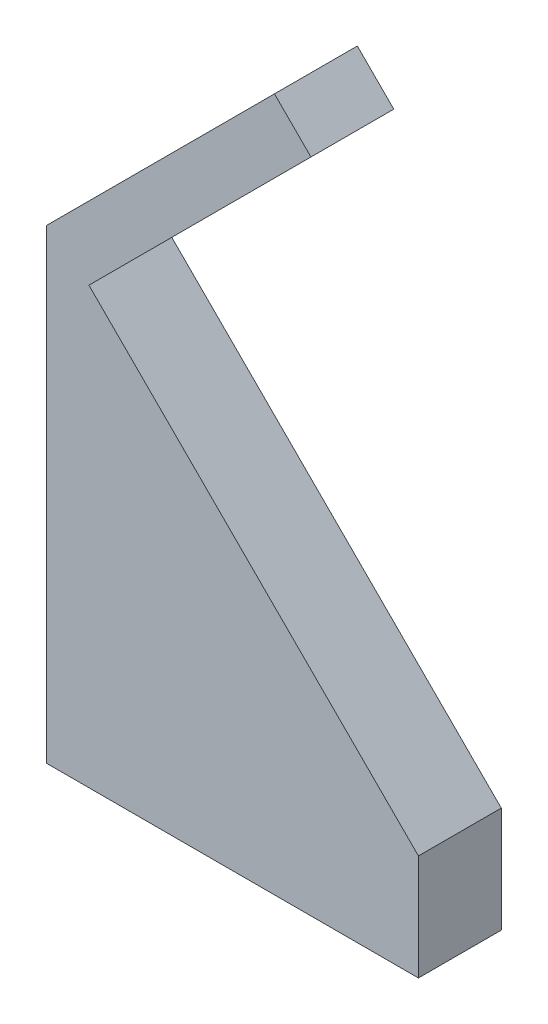
SolidWorks part; units mm, degrees
ref_plane "Alzado" through (0, 0, 0) normal (0, 0, 1) x (1, 0, 0)
ref_plane "Planta" through (0, 0, 0) normal (0, 1, 0) x (1, 0, 0)
ref_plane "Vista lateral" through (0, 0, 0) normal (1, 0, 0) x (0, 0, -1)
sketch "Croquis1" plane through (0, 0, 0) normal (0, 0, 1) x (1, 0, 0)
  line L0 (0, 61.867) -> (0, -61.867) construction
  line L1 (-5, 52.5879) -> (5, 52.5879) construction
  line L2 (-5, 52.5879) -> (-5, -52.5879) construction
  line L3 (-5, -52.5879) -> (5, -52.5879) construction
  line L4 (5, 52.5879) -> (5, -52.5879) construction
  line L5 (-5, 52.5879) -> (5, -52.5879) construction
  line L6 (-5, -52.5879) -> (5, 52.5879) construction
  line L7 (-5, -39.7902) -> (-5, -50)
  line L10 (-5, -50) -> (-40.8947, -50)
  line L11 (-40.8947, -5.0014) -> (-40.8947, -50)
  line L12 (-5, -39.7902) -> (-36.8198, -7.9704)
  line L14 (-36.8198, -7.9704) -> (-15.3793, 13.4701)
  line L16 (-15.3793, 13.4701) -> (-18.9013, 16.9921)
  line L17 (-18.9013, 16.9921) -> (-40.8947, -5.0014)
  circle A0 centre (0, 0) radius 30 construction
  point P10 (0, 0)
  dimension "D1" = 135
  dimension "D2" = 10
  dimension "D3" = 45
extrude "Saliente-Extruir1" add sketch "Croquis1" along normal blind 8
